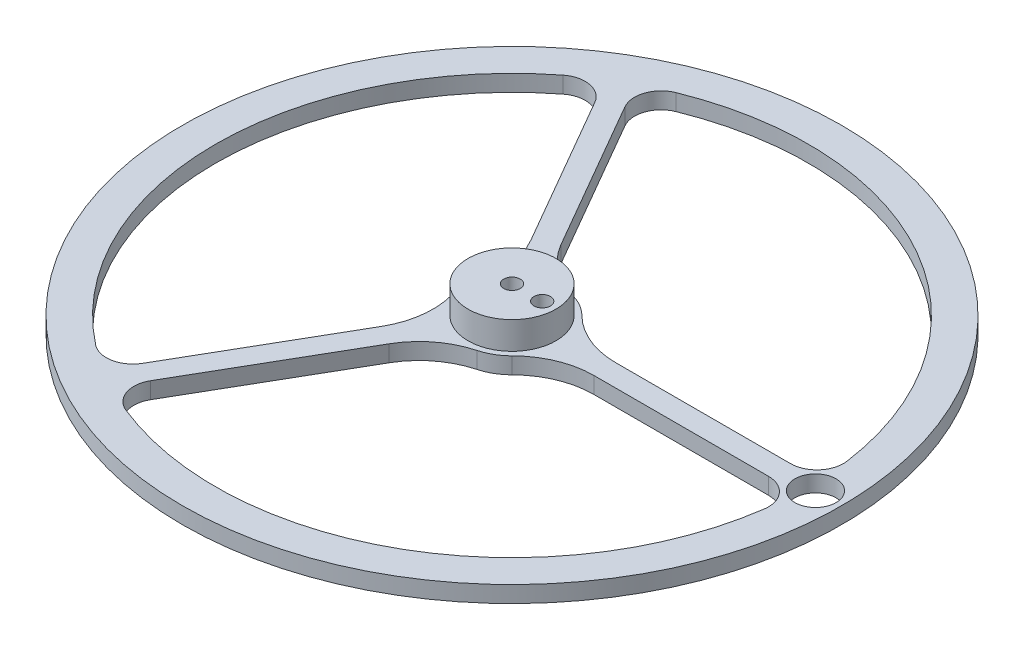
SolidWorks part; units mm, degrees
material "AISI 1020"
ref_plane "Front" through (0, 0, 0) normal (0, 0, 1) x (1, 0, 0)
ref_plane "Top" through (0, 0, 0) normal (0, 1, 0) x (1, 0, 0)
ref_plane "Right" through (0, 0, 0) normal (1, 0, 0) x (0, 0, -1)
sketch "Sketch1" plane through (0, 0, 0) normal (0, 1, 0) x (1, 0, 0)
  circle A0 centre (0, 0) radius 60
  circle A1 centre (0, 0) radius 54
  dimension "D1" = 120
  dimension "D2" = 6
extrude "Boss-Extrude1" add sketch "Sketch1" along normal blind 3
sketch "Sketch2" plane through (0, 0, 0) normal (0, 1, 0) x (1, 0, 0)
  circle A0 centre (0, 0) radius 9
  circle A1 centre (0, 0) radius 60 construction
  point P3 (0, 9)
  point P6 (0, -60)
  dimension "D1" = 69
extrude "Boss-Extrude2" add sketch "Sketch2" along normal blind 3 separate body
sketch "Sketch3" plane through (0, 3, 0) normal (0, 1, 0) x (1, 0, 0)
  circle A0 centre (0, 0) radius 8
  dimension "D1" = 16
extrude "Boss-Extrude3" add sketch "Sketch3" along normal blind 5
sketch "Sketch4" plane through (0, 0, 0) normal (0, 1, 0) x (1, 0, 0)
  line L0 (9, 0) -> (54, 0)
  line L1 (16.8995, -2) -> (48.6942, -2)
  line L2 (0, 0) -> (11.2327, -11.2327) construction
  circle A0 centre (0, 0) radius 9 construction
  circle A1 centre (0, 0) radius 54 construction
  arc A2 (48.6942, -2) -> (53.4766, -7.5) centre (48.6942, -6.8293) cw
  arc A3 (16.8995, -2) -> (6.364, -6.364) centre (16.8995, -16.8995) ccw
  arc A4 (6.364, -6.364) -> (9, 0) centre (0, 0) ccw
  arc A5 (53.4766, -7.5) -> (54, 0) centre (0, 0) ccw
  dimension "D1" = 45
  dimension "D2" = 7.5
  dimension "D3" = 2
extrude "Boss-Extrude4" add sketch "Sketch4" along normal up to surface (3 mm away) up to face at (0, 3, 60)
pattern_circular "CirPattern9" count 3 over 360 about axis through (0, 0, 0) along (0, 1, 0) of "Boss-Extrude4"
mirror "Mirror2" about plane through (-4.5, 54.4469, -7.7942) normal (0.866, 0, -0.5) of "CirPattern9", "Boss-Extrude4"
sketch "Sketch5" plane through (0, 8, 0) normal (0, 1, 0) x (1, 0, 0)
  circle A0 centre (5.5, 0) radius 1.5
  dimension "D2" = 3
  dimension "D1" = 5.5
extrude "Cut-Extrude1" cut sketch "Sketch5" against normal blind 5
sketch "Sketch6" plane through (0, 8, 0) normal (0, 1, 0) x (1, 0, 0)
  circle A0 centre (0, 0) radius 1.5
  dimension "D1" = 3
extrude "Cut-Extrude2" cut sketch "Sketch6" against normal through all both and the other way through all
sketch "Sketch7" plane through (0, 3, 0) normal (0, 1, 0) x (1, 0, 0)
  circle A0 centre (55.25, 0) radius 3.75
  point P2 (55.3035, 0)
  dimension "D1" = 7.5
  dimension "D2" = 55.25
extrude "Cut-Extrude3" cut sketch "Sketch7" against normal through all both and the other way through all
